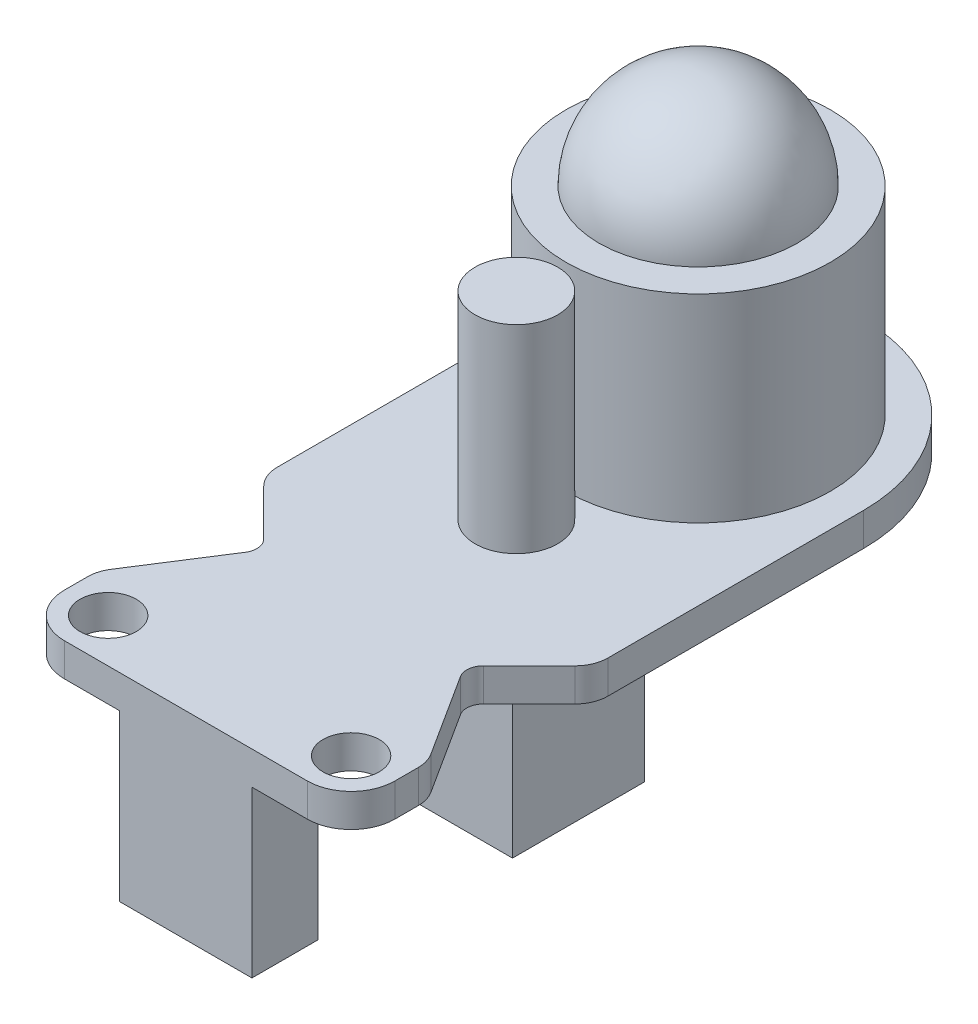
SolidWorks part; units mm, degrees
ref_plane "前视基准面" through (0, 0, 0) normal (0, 0, 1) x (1, 0, 0)
ref_plane "上视基准面" through (0, 0, 0) normal (0, 1, 0) x (1, 0, 0)
ref_plane "右视基准面" through (0, 0, 0) normal (1, 0, 0) x (0, 0, -1)
sketch "草图1" plane through (0, 0, 0) normal (0, 1, 0) x (1, 0, 0)
  line L0 (0, 0) -> (42.818, 0) construction
  line L1 (0, 0) -> (0, 39.1685) construction
  line L2 (10, 28.35) -> (10, 12.0642)
  line L3 (10, 12.0642) -> (6.6429, 8.7071)
  line L4 (6.5075, 7.4612) -> (10, 2)
  line L5 (10, 2) -> (10, 0)
  line L6 (7.35, -2.65) -> (-7.35, -2.65)
  line L7 (-10, 2) -> (-10, 0)
  line L8 (-6.5075, 7.4612) -> (-10, 2)
  line L9 (-10, 12.0642) -> (-6.6429, 8.7071)
  line L10 (-10, 28.35) -> (-10, 12.0642)
  arc A0 (7.35, -2.65) -> (10, 0) centre (7.35, 0) ccw
  arc A1 (10, 28.35) -> (-10, 28.35) centre (0, 28.35) ccw
  arc A2 (6.6429, 8.7071) -> (6.5075, 7.4612) centre (7.35, 8) ccw
  circle A3 centre (7.35, 0) radius 1.7
  circle A4 centre (-7.35, 0) radius 1.7
  arc A5 (-6.6429, 8.7071) -> (-6.5075, 7.4612) centre (-7.35, 8) cw
  arc A6 (-7.35, -2.65) -> (-10, 0) centre (-7.35, 0) cw
  point P24 (0, -2.65)
  point P26 (0, 38.35)
  point P27 (0, 0)
  point P28 (7.5303, 7.0086)
  point P29 (10, 3.5796)
  point P30 (10, 9.847)
  point P31 (10, 1.813)
  point P32 (7.35, 6.3519)
  dimension "D1" = 41
  dimension "D4" = 1
  dimension "D5" = 3.4
  dimension "D2" = 14.7
  dimension "D3" = 20
  dimension "D6" = 135
  dimension "D7" = 8
  dimension "D8" = 2
extrude "凸台-拉伸1" add sketch "草图1" along normal blind 2
fillet "圆角1" radius 2 4 edges at (10, 1, -2) (10, 1, -12.0642) (-10, 1, -2) (-10, 1, -12.0642)
sketch "草图3" plane through (0, 2, 0) normal (0, 1, 0) x (1, 0, 0)
  circle A0 centre (0, 28.35) radius 8
  circle A1 centre (0, 17.35) radius 2.5
  dimension "D1" = 5
  dimension "D2" = 16
  dimension "D3" = 11
extrude "凸台-拉伸2" add sketch "草图3" along normal blind 12
sketch "草图4" plane through (0, 14, 0) normal (0, 1, 0) x (1, 0, 0)
  line L0 (0, 36.0536) -> (0, 20.35) construction
  line L1 (0, 34.35) -> (0, 22.35)
  circle A0 centre (0, 28.35) radius 8 construction
  arc A2 (0, 22.35) -> (0, 34.35) centre (0, 28.35) ccw
  dimension "D1" = 12
revolve "旋转1" add sketch "草图4" angle 360 about L0
sketch "草图5" plane through (0, 0, 0) normal (0, -1, 0) x (1, 0, 0)
  line L1 (3.6017, -21.5135) -> (-4.3983, -21.5135)
  line L2 (3.6017, -21.5135) -> (3.6017, -13.5135)
  line L3 (3.6017, -13.5135) -> (-4.3983, -13.5135)
  line L4 (-4.3983, -21.5135) -> (-4.3983, -13.5135)
  line L5 (3.6017, -21.5135) -> (-4.3983, -13.5135) construction
  line L6 (3.6017, -13.5135) -> (-4.3983, -21.5135) construction
  point P0 (-0.3983, -17.5135)
  dimension "D1" = 8
  dimension "D2" = 8
extrude "凸台-拉伸3" add sketch "草图5" along normal blind 12
sketch "草图6" plane through (0, 0, 0) normal (0, -1, 0) x (1, 0, 0)
  line L0 (-7.35, 2.65) -> (7.35, 2.65) construction
  line L1 (4, -1.35) -> (-4, -1.35)
  line L2 (4, -1.35) -> (4, 2.65)
  line L3 (4, 2.65) -> (-4, 2.65)
  line L4 (-4, -1.35) -> (-4, 2.65)
  line L5 (4, -1.35) -> (-4, 2.65) construction
  line L6 (4, 2.65) -> (-4, -1.35) construction
  point P0 (0, 0.65)
  point P5 (0, 0)
  dimension "D1" = 8
  dimension "D2" = 4
extrude "凸台-拉伸4" add sketch "草图6" along normal blind 10
